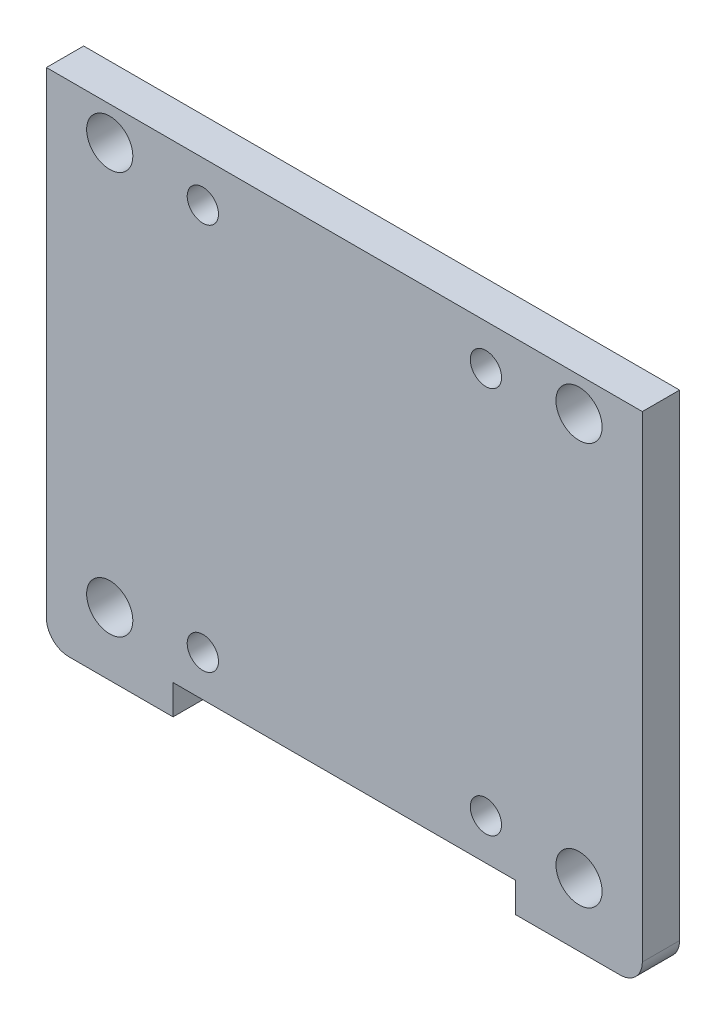
SolidWorks part; units mm, degrees
material "Thornel Mat VMA"
ref_plane "前视基准面" through (0, 0, 0) normal (0, 0, 1) x (1, 0, 0)
ref_plane "上视基准面" through (0, 0, 0) normal (0, 1, 0) x (1, 0, 0)
ref_plane "右视基准面" through (0, 0, 0) normal (1, 0, 0) x (0, 0, -1)
sketch "草图1" plane through (0, 0, 0) normal (0, 0, 1) x (1, 0, 0)
  line L1 (-37, -35.5) -> (37, -35.5)
  line L2 (-40, -32.5) -> (-40, 32.5)
  line L3 (-37, 35.5) -> (37, 35.5)
  line L4 (40, -32.5) -> (40, 32.5)
  line L5 (-40, -35.5) -> (40, 35.5) construction
  line L6 (-40, 35.5) -> (40, -35.5) construction
  arc A0 (37, -35.5) -> (40, -32.5) centre (37, -32.5) ccw
  arc A1 (-40, 32.5) -> (-37, 35.5) centre (-37, 32.5) cw
  arc A2 (-37, -35.5) -> (-40, -32.5) centre (-37, -32.5) cw
  arc A3 (37, 35.5) -> (40, 32.5) centre (37, 32.5) cw
  point P0 (0, 0)
  dimension "D3" = 3
  dimension "D1" = 71
  dimension "D2" = 80
extrude "凸台-拉伸1" add sketch "草图1" along normal blind 5
sketch "草图2" plane through (0, 0, 5) normal (0, 0, 1) x (1, 0, 0)
  line L1 (-31.5, -27) -> (31.5, -27) construction
  line L2 (-31.5, -27) -> (-31.5, 27) construction
  line L3 (-31.5, 27) -> (31.5, 27) construction
  line L4 (31.5, -27) -> (31.5, 27) construction
  line L5 (-31.5, -27) -> (31.5, 27) construction
  line L6 (-31.5, 27) -> (31.5, -27) construction
  circle A0 centre (-31.5, 27) radius 3.1
  circle A1 centre (31.5, 27) radius 3.1
  circle A2 centre (31.5, -27) radius 3.1
  circle A3 centre (-31.5, -27) radius 3.1
  point P0 (0, 0)
  dimension "D3" = 6.2
  dimension "D1" = 54
  dimension "D2" = 63
extrude "切除-拉伸1" cut sketch "草图2" against normal blind 5
sketch "草图3" plane through (0, 0, 5) normal (0, 0, 1) x (1, 0, 0)
  line L0 (-37, -35.5) -> (37, -35.5) construction
  line L1 (-23, -39.5) -> (23, -39.5)
  line L2 (-23, -39.5) -> (-23, -31.5)
  line L3 (-23, -31.5) -> (23, -31.5)
  line L4 (23, -39.5) -> (23, -31.5)
  line L5 (-23, -39.5) -> (23, -31.5) construction
  line L6 (-23, -31.5) -> (23, -39.5) construction
  line L7 (37, 35.5) -> (-37, 35.5) construction
  line L8 (-40, 31.5) -> (40, 31.5)
  line L9 (-40, 31.5) -> (-40, 39.5)
  line L10 (-40, 39.5) -> (40, 39.5)
  line L11 (40, 31.5) -> (40, 39.5)
  line L12 (-40, 31.5) -> (40, 39.5) construction
  line L13 (-40, 39.5) -> (40, 31.5) construction
  point P0 (0, -35.5)
  point P7 (0, 35.5)
  dimension "D1" = 46
  dimension "D2" = 4
  dimension "D3" = 80
  dimension "D4" = 4
extrude "切除-拉伸2" cut sketch "草图3" against normal blind 5
sketch "草图4" plane through (0, 0, 5) normal (0, 0, 1) x (1, 0, 0)
  circle A0 centre (19, -26) radius 2.1 construction
  circle A1 centre (-19, -26) radius 2.1 construction
  circle A2 centre (-19, 26) radius 2.1 construction
  circle A3 centre (19, 26) radius 2.1 construction
  circle A4 centre (19, -26) radius 2.1
  circle A5 centre (-19, -26) radius 2.1
  circle A6 centre (-19, 26) radius 2.1
  circle A7 centre (19, 26) radius 2.1
extrude "切除-拉伸3" cut sketch "草图4" against normal through all
sketch "草图5" plane through (0, 0, 0) normal (0, 0, -1) x (-1, 0, 0)
  circle A0 centre (19, 26) radius 2.1 construction
  circle A1 centre (-19, 26) radius 2.1 construction
  circle A2 centre (-19, -26) radius 2.1 construction
  circle A3 centre (19, -26) radius 2.1 construction
  circle A4 centre (19, 26) radius 2.1
  circle A5 centre (-19, 26) radius 2.1
  circle A6 centre (-19, -26) radius 2.1
  circle A7 centre (19, -26) radius 2.1
